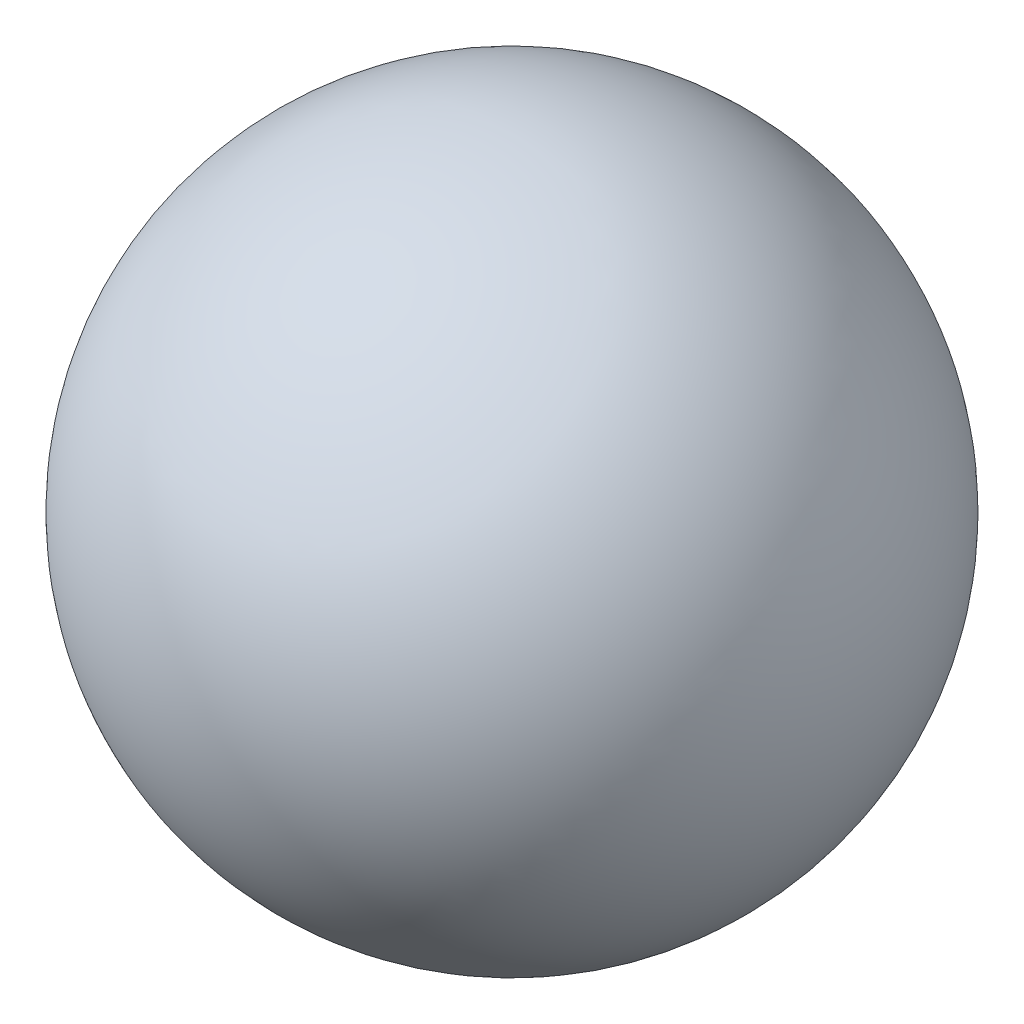
SolidWorks part; units mm, degrees
ref_plane "Front" through (0, 0, 0) normal (0, 0, 1) x (1, 0, 0)
ref_plane "Top" through (0, 0, 0) normal (0, 1, 0) x (1, 0, 0)
ref_plane "Right" through (0, 0, 0) normal (1, 0, 0) x (0, 0, -1)
sketch "Sketch2" plane through (0, 0, 0) normal (0, 1, 0) x (1, 0, 0)
  line L0 (0, 0) -> (0, 8) construction
  line L1 (0, 7.5) -> (3.3833, 7.5) construction
  line L2 (1.9365, 7.5) -> (0, 7.5)
  line L3 (0, 7.5) -> (0, 0)
  arc A0 (0, 8) -> (0, 0) centre (0, 4) cw construction
  arc A1 (1.9365, 7.5) -> (0, 0) centre (0, 4) cw
  dimension "D1" = 8
  dimension "D2" = 0.5
revolve "Revolve1" add sketch "Sketch2" angle 360 about L3
hole_wizard "M3x0.5 Tapped Hole1" positions "Sketch3" profile "Sketch5" tap size "M3x0.5" standard "ANSI Metric"
sketch "Sketch3" plane through (0, 0, -7.5) normal (0, 0, -1) x (-1, 0, 0)
  point P3 (0, 0)
sketch "Sketch5" plane through (0, 0, -7.5) normal (1, 0, 0) x (0, 1, 0)
  line L0 (0, 0) -> (0, 5.7511)
  line L1 (0, 5.7511) -> (1.25, 5)
  line L2 (1.25, 5) -> (1.25, 0)
  line L5 (1.25, 0) -> (0, 0)
  line L10 (0, 5.7511) -> (-1.25, 5) construction
  line L11 (0, -6.35) -> (0, 107.95) construction
  dimension "Tap Drill Dia." = 2.5
  dimension "Tap Drill Depth" = 5
  dimension "Drill Angle" = 118
cosmetic thread "Hole Thread1" parameters "D1"=6, "D2"=3
